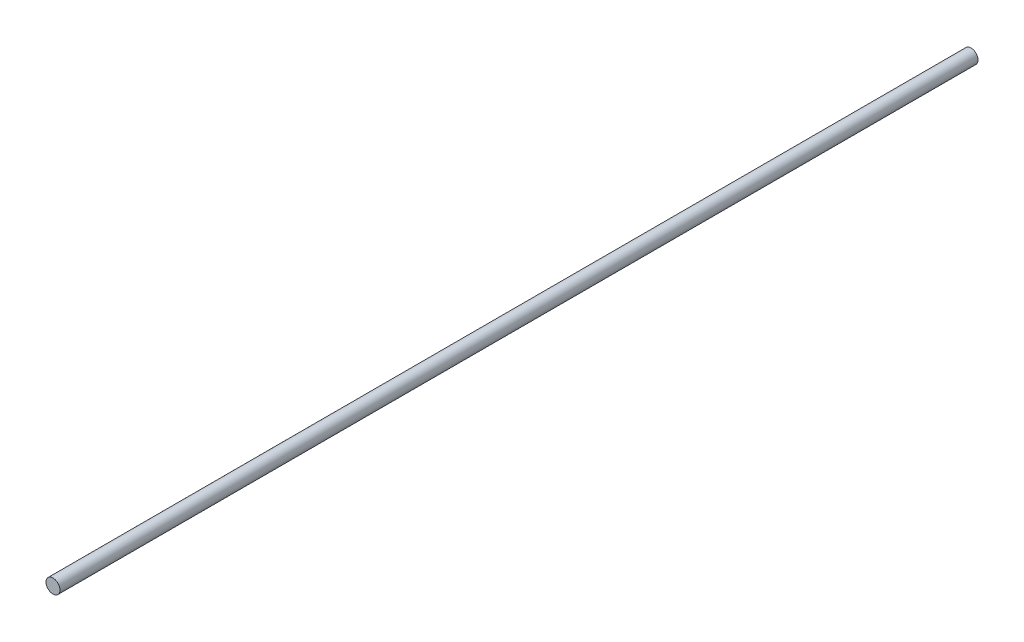
SolidWorks part; units mm, degrees
ref_plane "Plan de face" through (0, 0, 0) normal (0, 0, 1) x (1, 0, 0)
ref_plane "Plan de dessus" through (0, 0, 0) normal (0, 1, 0) x (1, 0, 0)
ref_plane "Plan de droite" through (0, 0, 0) normal (1, 0, 0) x (0, 0, -1)
sketch "Esquisse1" plane through (0, 0, 0) normal (0, 0, 1) x (1, 0, 0)
  circle A0 centre (0, 0) radius 5
  dimension "D1" = 10
extrude "Boss.-Extru.1" add sketch "Esquisse1" along normal blind 658
